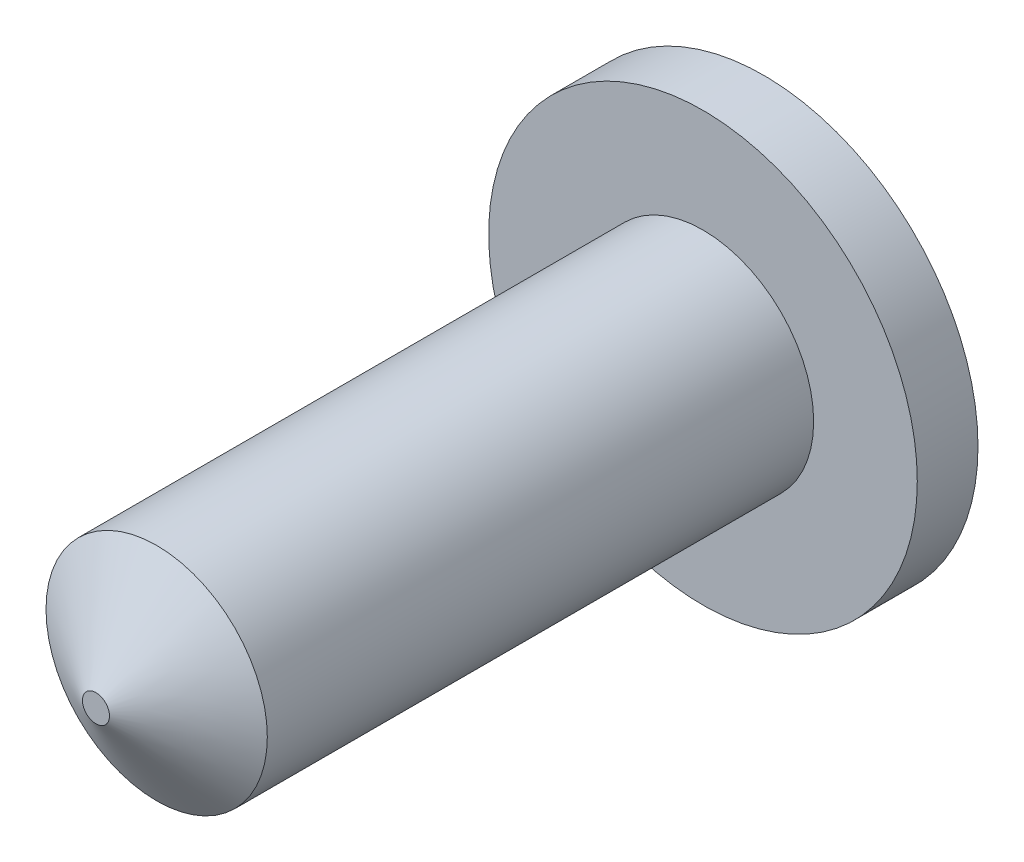
SolidWorks part; units mm, degrees
ref_plane "Front Plane" through (0, 0, 0) normal (0, 0, 1) x (1, 0, 0)
ref_plane "Top Plane" through (0, 0, 0) normal (0, 1, 0) x (1, 0, 0)
ref_plane "Right Plane" through (0, 0, 0) normal (1, 0, 0) x (0, 0, -1)
sketch "Sketch1" plane through (0, 0, 0) normal (0, 0, 1) x (1, 0, 0)
  circle A0 centre (0, 0) radius 35.3042
extrude "Boss-Extrude1" add sketch "Sketch1" along normal blind 10
sketch "Sketch2" plane through (0, 0, 10) normal (0, 0, 1) x (1, 0, 0)
  circle A0 centre (0, 0) radius 18.2293
extrude "Boss-Extrude2" add sketch "Sketch2" along normal blind 100
chamfer "Chamfer1" distance 10 angle 58 1 edges at (18.2293, 0, 110)
